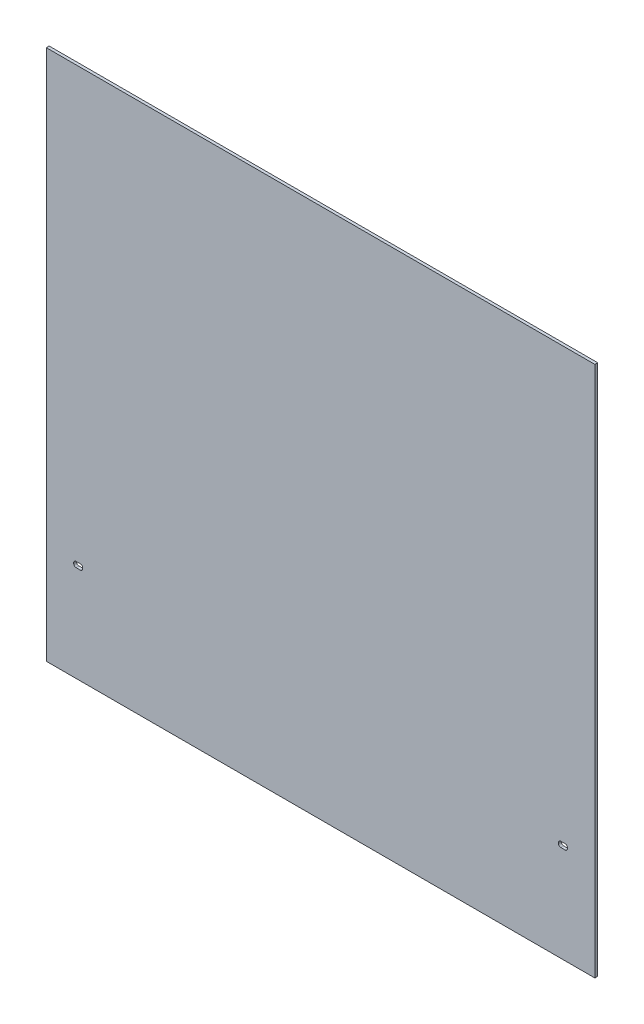
SolidWorks part; units mm, degrees
ref_plane "Front Plane" through (0, 0, 0) normal (0, 0, 1) x (1, 0, 0)
ref_plane "Top Plane" through (0, 0, 0) normal (0, 1, 0) x (1, 0, 0)
ref_plane "Right Plane" through (0, 0, 0) normal (1, 0, 0) x (0, 0, -1)
sketch "Sketch1" plane through (0, 0, 0) normal (0, 0, 1) x (1, 0, 0)
  line L0 (-579.12, 109.18) -> (-579.12, 110.18)
  line L1 (0, 0) -> (-609.6, 0)
  line L2 (0, 0) -> (0, 590.55)
  line L3 (0, 590.55) -> (-609.6, 590.55)
  line L4 (-609.6, 0) -> (-609.6, 590.55)
  line L5 (-576.62, 112.68) -> (-571.62, 112.68)
  line L6 (-569.12, 109.18) -> (-569.12, 110.18)
  line L7 (-576.62, 106.68) -> (-571.62, 106.68)
  line L8 (-304.8, 590.55) -> (-304.8, 0) construction
  line L9 (-32.98, 106.68) -> (-37.98, 106.68)
  line L10 (-40.48, 109.18) -> (-40.48, 110.18)
  line L11 (-32.98, 112.68) -> (-37.98, 112.68)
  line L12 (-30.48, 109.18) -> (-30.48, 110.18)
  arc A0 (-579.12, 110.18) -> (-576.62, 112.68) centre (-576.62, 110.18) cw
  arc A1 (-569.12, 110.18) -> (-571.62, 112.68) centre (-571.62, 110.18) ccw
  arc A2 (-571.62, 106.68) -> (-569.12, 109.18) centre (-571.62, 109.18) ccw
  arc A3 (-579.12, 109.18) -> (-576.62, 106.68) centre (-576.62, 109.18) ccw
  arc A4 (-30.48, 109.18) -> (-32.98, 106.68) centre (-32.98, 109.18) cw
  arc A5 (-37.98, 106.68) -> (-40.48, 109.18) centre (-37.98, 109.18) cw
  arc A6 (-40.48, 110.18) -> (-37.98, 112.68) centre (-37.98, 110.18) cw
  arc A7 (-30.48, 110.18) -> (-32.98, 112.68) centre (-32.98, 110.18) ccw
  dimension "D11" = 2.5
  dimension "D1" = 590.55
  dimension "D2" = 609.6
  dimension "D6" = 106.68
  dimension "D7" = 30.48
  dimension "D8" = 1
  dimension "D12" = 5
extrude "Boss-Extrude1" add sketch "Sketch1" along normal blind 3.175
